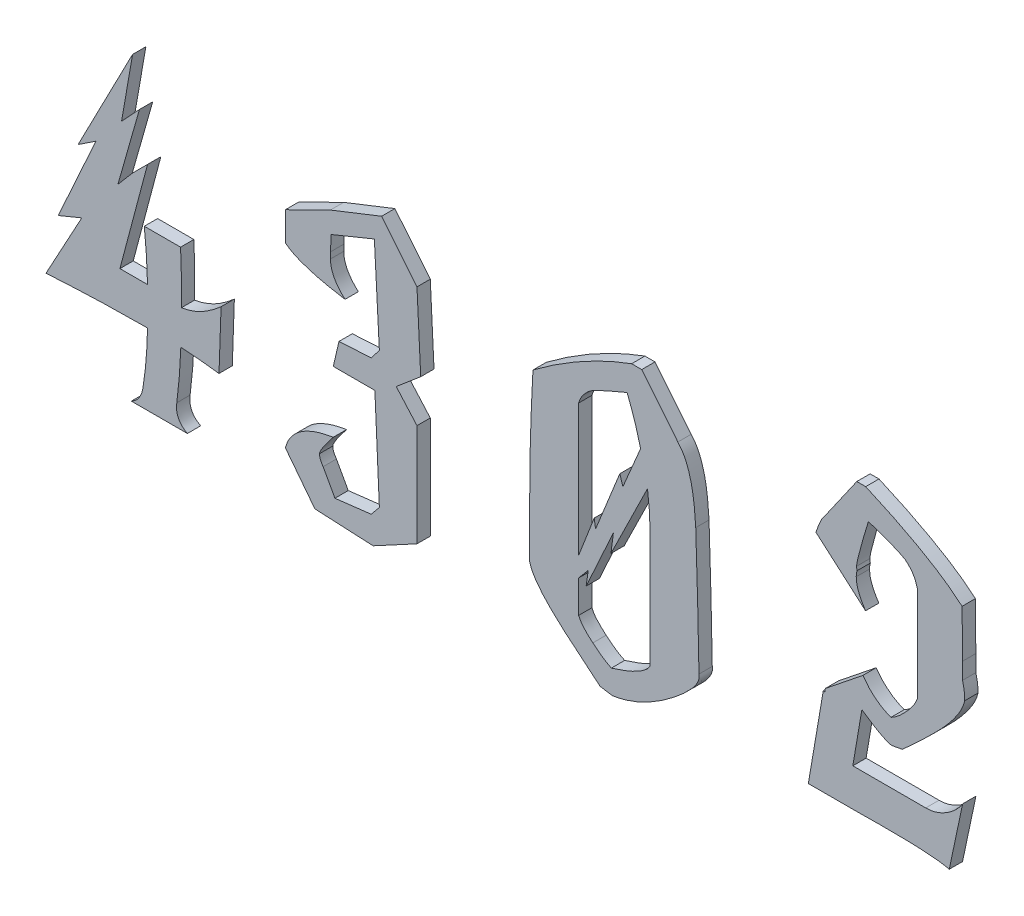
SolidWorks part; units mm, degrees
ref_plane "Front Plane" through (0, 0, 0) normal (0, 0, 1) x (1, 0, 0)
ref_plane "Top Plane" through (0, 0, 0) normal (0, 1, 0) x (1, 0, 0)
ref_plane "Right Plane" through (0, 0, 0) normal (1, 0, 0) x (0, 0, -1)
sketch "Sketch1" plane through (0, 0, 0) normal (0, 0, 1) x (1, 0, 0)
  text T0 "4" font "Harry P" height in points 225
extrude "4" add sketch "Sketch1" along normal blind 3.175
sketch "Sketch3" plane through (0, 0, 0) normal (0, 0, 1) x (1, 0, 0)
  text T0 "3" font "Harry P" height in points 225
extrude "3" add sketch "Sketch3" along normal blind 3.175 separate body
sketch "Sketch4" plane through (0, 0, 3.175) normal (0, 0, 1) x (1, 0, 0)
  text T0 "0" font "Harry P" height in points 225
extrude "0" add sketch "Sketch4" along normal blind 3.175 separate body
sketch "Sketch5" plane through (0, 0, 0) normal (0, 0, 1) x (1, 0, 0)
  text T0 "2" font "Harry P" height in points 225
extrude "2" add sketch "Sketch5" along normal blind 3.175 separate body
